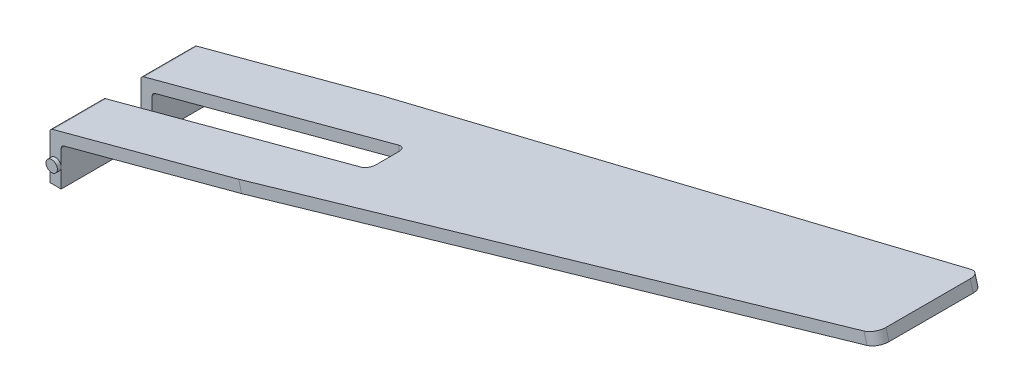
SolidWorks part; units mm, degrees
ref_plane "Front Plane" through (0, 0, 0) normal (0, 0, 1) x (1, 0, 0)
ref_plane "Top Plane" through (0, 0, 0) normal (0, 1, 0) x (1, 0, 0)
ref_plane "Right Plane" through (0, 0, 0) normal (1, 0, 0) x (0, 0, -1)
sketch "Profile Sketch" plane through (0, 0, 0) normal (0, 0, 1) x (1, 0, 0)
  line L0 (0, 0) -> (0, 1.2302)
  line L1 (0, 1.2302) -> (21.2504, 6.9242)
  line L2 (21.2504, 6.9242) -> (21.328, 6.6344)
  line L3 (21.328, 6.6344) -> (0.3, 1)
  line L4 (0.3, 1) -> (0.3, 0)
  line L5 (0.3, 0) -> (0, 0)
  dimension "D1" = 0.3
  dimension "D2" = 0.3
  dimension "D3" = 1
  dimension "D4" = 105
  dimension "D5" = 22
extrude "Profile Extrude" add sketch "Profile Sketch" along normal blind 3.8
chamfer "Chamfer Top" distance 0.5 angle 88.3 2 edges at (21.2892, 6.7793, 3.8) (21.2892, 6.7793, 0)
sketch "Sketch3" plane through (0, 0, 3.8) normal (0, 0, 1) x (1, 0, 0)
  circle A0 centre (0.15, 0.5) radius 0.15
  dimension "D1" = 0.3
  dimension "D2" = 0.15
  dimension "D3" = 0.5
extrude "Pins Extrude" add sketch "Sketch3" along normal blind 0.1 and the other way blind 3.9
sketch "Slot Sketch" plane through (0, 0, 0) normal (0, -1, 0) x (1, 0, 0)
  line L0 (0, 3.8) -> (0, 0) construction
  line L1 (0, 2.4) -> (7, 2.4)
  line L2 (0, 2.4) -> (0, 1.4)
  line L3 (0, 1.4) -> (7, 1.4)
  line L4 (7, 2.4) -> (7, 1.4)
  line L5 (0, 0) -> (0.3, 0) construction
  point P6 (7, 1.9)
  dimension "D1" = 7
  dimension "D2" = 1
  dimension "D3" = 1.9
extrude "Slot Cut" cut sketch "Slot Sketch" against normal blind 10
fillet "Fillet1" radius 0.1 4 edges at (0, 1.2302, 0.7) (0, 1.2302, 3.1) (0.3, 1, 0.7) (0.3, 1, 3.1)
fillet "Fillet2" radius 0.3 2 edges at (21.2892, 6.7793, 0.5) (21.2892, 6.7793, 3.3)
fillet "Fillet3" radius 0.2 2 edges at (7, 2.9506, 2.4) (7, 2.9506, 1.4)
